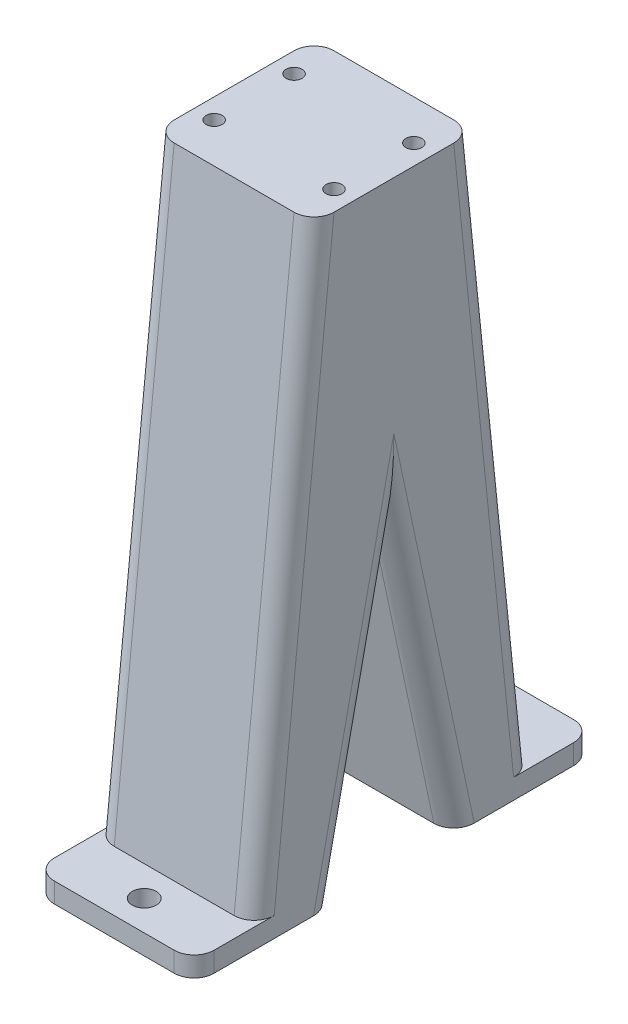
SolidWorks part; units mm, degrees
ref_plane "Front Plane" through (0, 0, 0) normal (0, 0, 1) x (1, 0, 0)
ref_plane "Top Plane" through (0, 0, 0) normal (0, 1, 0) x (1, 0, 0)
ref_plane "Right Plane" through (0, 0, 0) normal (1, 0, 0) x (0, 0, -1)
sketch "Sketch1" plane through (0, 0, 0) normal (1, 0, 0) x (0, 0, -1)
  line L11 (0, 0) -> (0, 150) construction
  line L12 (-20, 150) -> (20, 150)
  line L13 (20, 150) -> (35, 5)
  line L14 (35, 5) -> (50, 5)
  line L15 (50, 5) -> (50, 0)
  line L16 (50, 0) -> (15, 0)
  line L17 (15, 0) -> (0, 70.5288)
  line L18 (0, 70.5288) -> (-15, 0)
  line L19 (-15, 0) -> (-50, 0)
  line L20 (-50, 0) -> (-50, 5)
  line L21 (-50, 5) -> (-35, 5)
  line L22 (-35, 5) -> (-20, 150)
  point P6 (0, 150)
  dimension "D1" = 15
  dimension "D2" = 5
  dimension "D3" = 100
  dimension "D4" = 150
  dimension "D5" = 40
  dimension "D6" = 35
extrude "Boss-Extrude1" add sketch "Sketch1" along normal blind 40
sketch "Sketch2" plane through (0, 5, 0) normal (0, 1, 0) x (1, 0, 0)
  line L0 (40, -50) -> (0, -50) construction
  line L1 (40, -35) -> (40, -50) construction
  line L2 (40, 50) -> (40, 35) construction
  circle A0 centre (20, 42.5) radius 3
  circle A1 centre (20, -42.5) radius 3
  point P7 (20, -50)
  point P10 (40, -42.5)
  point P13 (40, 42.5)
  dimension "D1" = 6
extrude "Cut-Extrude1" cut sketch "Sketch2" against normal blind 40
sketch "Sketch3" plane through (0, 150, 0) normal (0, 1, 0) x (1, 0, 0)
  line L0 (40, 20) -> (0, 20) construction
  line L1 (5, -10) -> (35, -10)
  line L2 (5, -10) -> (5, 10)
  line L3 (5, 10) -> (35, 10)
  line L4 (35, -10) -> (35, 10)
  line L5 (5, -10) -> (35, 10) construction
  line L6 (5, 10) -> (35, -10) construction
  circle A0 centre (35, 10) radius 2
  circle A1 centre (35, -10) radius 2
  circle A2 centre (5, -10) radius 2
  circle A3 centre (5, 10) radius 2
  point P0 (20, 0)
  point P10 (20, 20)
  dimension "D3" = 4
  dimension "D1" = 20
  dimension "D2" = 30
extrude "Cut-Extrude2" cut sketch "Sketch3" against normal blind 40 contours L1 A1 L4 | L4 A1 L1 | L3 A0 L4 | L4 A0 L3 | L3 A3 L2 | L2 A3 L3 | L2 A2 L1 | L1 A2 L2
fillet "Fillet1" radius 5 12 edges at (0, 35.2644, 7.5) (0, 35.2644, -7.5) (0, 77.5, -27.5) (0, 2.5, -50) (0, 77.5, 27.5) (0, 2.5, 50) (40, 2.5, -50) (40, 77.5, -27.5) (40, 35.2644, -7.5) (40, 35.2644, 7.5) (40, 2.5, 50) (40, 77.5, 27.5)
